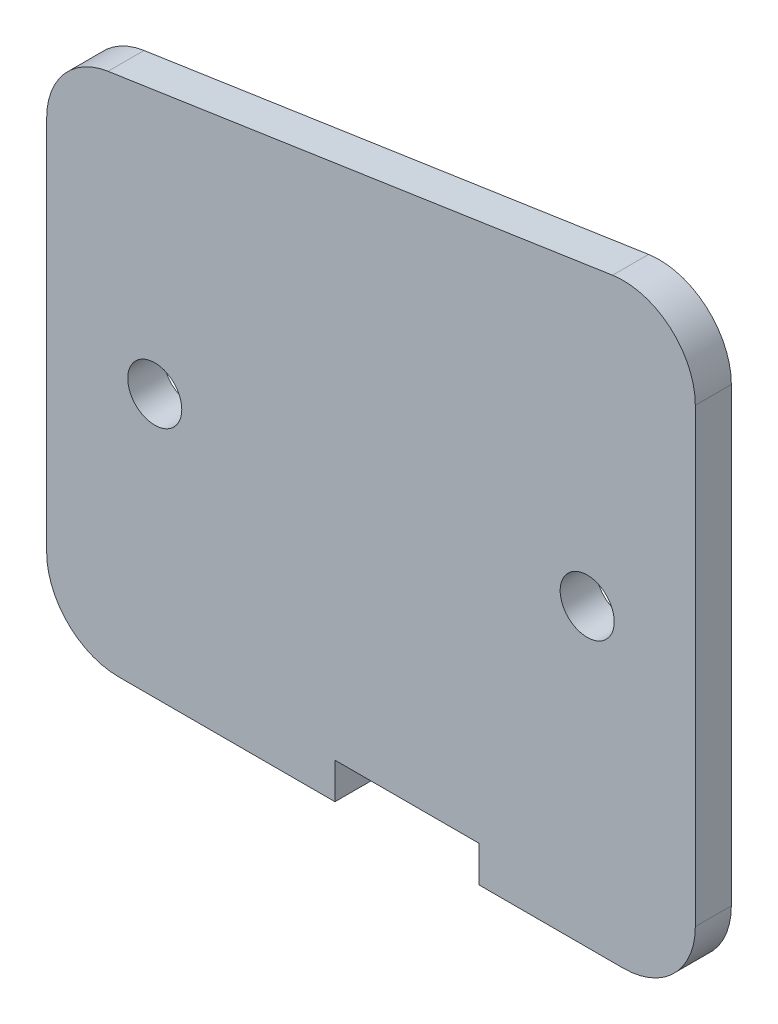
SolidWorks part; units mm, degrees
ref_plane "Front Plane" through (0, 0, 0) normal (0, 0, 1) x (1, 0, 0)
ref_plane "Top Plane" through (0, 0, 0) normal (0, 1, 0) x (1, 0, 0)
ref_plane "Right Plane" through (0, 0, 0) normal (1, 0, 0) x (0, 0, -1)
sketch "Sketch1" plane through (0, 0, 0) normal (0, 0, 1) x (1, 0, 0)
  line L0 (-118.417, 45.7375) -> (-73.967, 52.405)
  line L1 (-98.425, 0) -> (-117.475, 0)
  line L5 (-76.2, 0) -> (-76.2, 52.07)
  line L6 (-114.3, 0) -> (-114.3, 46.355)
  line L13 (-66.675, 46.1252) -> (-66.675, 6.35)
  line L14 (-123.825, 39.4577) -> (-123.825, 6.35)
  line L17 (-98.425, 0) -> (-98.425, 3.175)
  line L18 (-98.425, 3.175) -> (-85.725, 3.175)
  line L19 (-85.725, 0) -> (-85.725, 3.175)
  line L20 (-73.025, 0) -> (-85.725, 0)
  circle A0 centre (-114.3, 23.1775) radius 2.3813
  circle A1 centre (-76.2, 26.035) radius 2.3813
  arc A2 (-123.825, 6.35) -> (-117.475, 0) centre (-117.475, 6.35) ccw
  arc A3 (-66.675, 6.35) -> (-73.025, 0) centre (-73.025, 6.35) cw
  arc A4 (-66.675, 46.1252) -> (-73.967, 52.405) centre (-73.025, 46.1252) ccw
  arc A5 (-123.825, 39.4577) -> (-118.417, 45.7375) centre (-117.475, 39.4577) cw
  dimension "D8" = 4.7625
  dimension "D9" = 4.7625
  dimension "D2" = 6.35
  dimension "D6" = 9.525
  dimension "D7" = 9.525
  dimension "D10" = 12.7
  dimension "D11" = 3.175
  dimension "D12" = 19.05
  dimension "D13" = 38.1
extrude "Boss-Extrude1" add sketch "Sketch1" along normal blind 3.175 contours A5 L14 A2 L1 L6 A0 L0 | A1 L5 L0 L6 A0 L1 L17 L18 L19 L20 | L13 A4 L0 L5 A1 L20 A3
